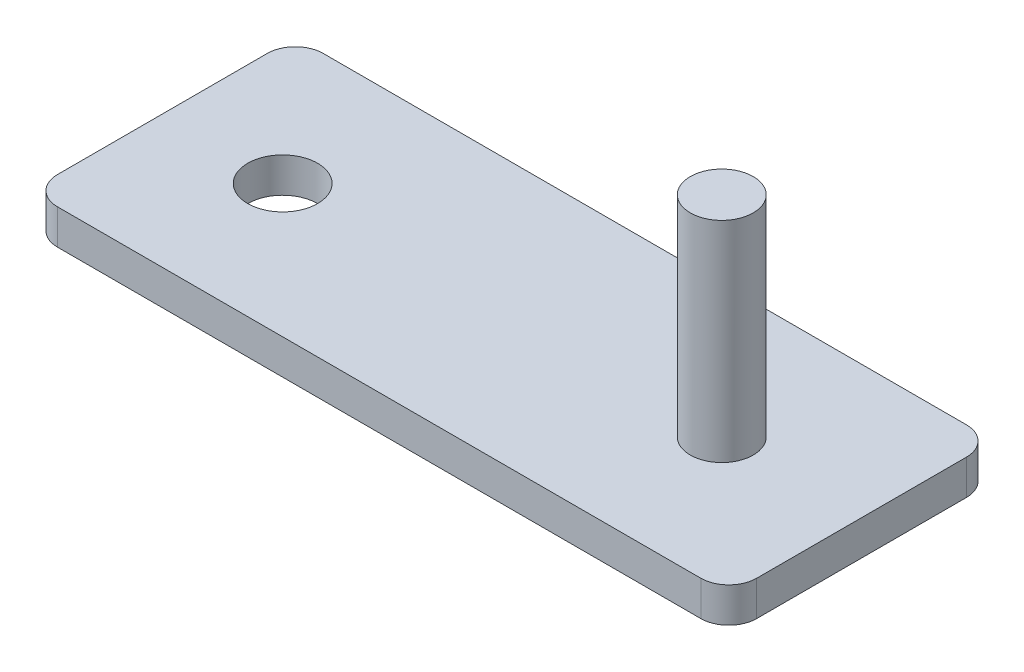
SolidWorks part; units mm, degrees
material "ABS"
ref_plane "Front Plane" through (0, 0, 0) normal (0, 0, 1) x (1, 0, 0)
ref_plane "Top Plane" through (0, 0, 0) normal (0, 1, 0) x (1, 0, 0)
ref_plane "Right Plane" through (0, 0, 0) normal (1, 0, 0) x (0, 0, -1)
sketch "Sketch1" plane through (0, 0, 0) normal (0, 1, 0) x (1, 0, 0)
  line L1 (0, 0) -> (50, 0)
  line L2 (0, 0) -> (0, 19)
  line L3 (0, 19) -> (50, 19)
  line L4 (50, 0) -> (50, 19)
  circle A0 centre (8.6, 9.5) radius 2.5
  dimension "D2" = 5
  dimension "D3" = 8.6
  dimension "D1" = 19
  dimension "D4" = 9.5
  dimension "D5" = 50
extrude "Base Plate" add sketch "Sketch1" along normal blind 2.5
sketch "Sketch2" plane through (0, 2.5, 0) normal (0, 1, 0) x (1, 0, 0)
  line L0 (50, 0) -> (50, 19) construction
  line L1 (50, 19) -> (0, 19) construction
  circle A0 centre (40, 9.5) radius 2.25
  dimension "D1" = 4.5
  dimension "D2" = 10
  dimension "D3" = 9.5
extrude "Axis" add sketch "Sketch2" along normal blind 15
fillet "Fillet1" radius 2 4 edges at (50, 1.25, -19) (50, 1.25, 0) (0, 1.25, 0) (0, 1.25, -19)
